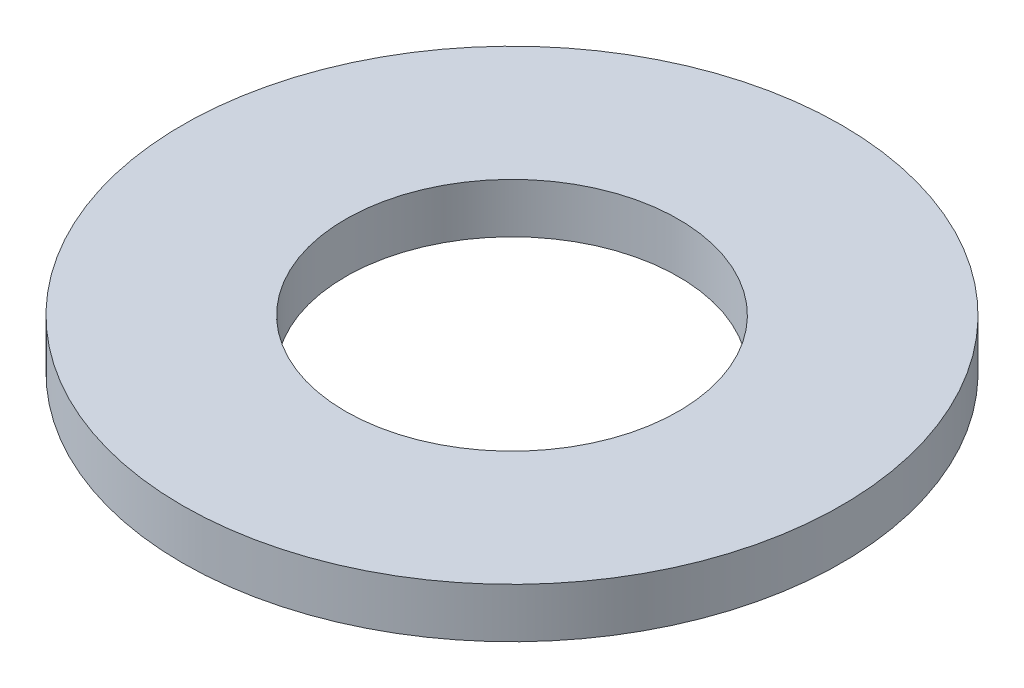
SolidWorks part; units mm, degrees
ref_plane "Front Plane" through (0, 0, 0) normal (0, 0, 1) x (1, 0, 0)
ref_plane "Top Plane" through (0, 0, 0) normal (0, 1, 0) x (1, 0, 0)
ref_plane "Right Plane" through (0, 0, 0) normal (1, 0, 0) x (0, 0, -1)
sketch "Sketch1" plane through (0, 0, 0) normal (0, 1, 0) x (1, 0, 0)
  circle A1 centre (0, 0) radius 3.3655
  dimension "D1" = 6.731
extrude "Boss-Extrude1" add sketch "Sketch1" along normal blind 0.508
hole_wizard "M3 Clearance Hole1" positions "Sketch2" profile "Sketch4" hole size "M3" standard "ANSI Metric" end condition through all
sketch "Sketch2" plane through (0, 0.508, 0) normal (0, 1, 0) x (1, 0, 0)
  point P0 (0, 0)
sketch "Sketch4" plane through (0, 0.508, 0) normal (1, 0, 0) x (0, 0, 1)
  line L0 (0, 0) -> (0, 0.508)
  line L1 (0, 0.508) -> (1.7, 0.508)
  line L2 (1.7, 0.508) -> (1.7, 0)
  line L5 (1.7, 0) -> (0, 0)
  line L11 (0, -6.35) -> (0, 107.95) construction
  dimension "Thru Hole Dia." = 3.4
  dimension "Thru Hole Depth" = 0.508
